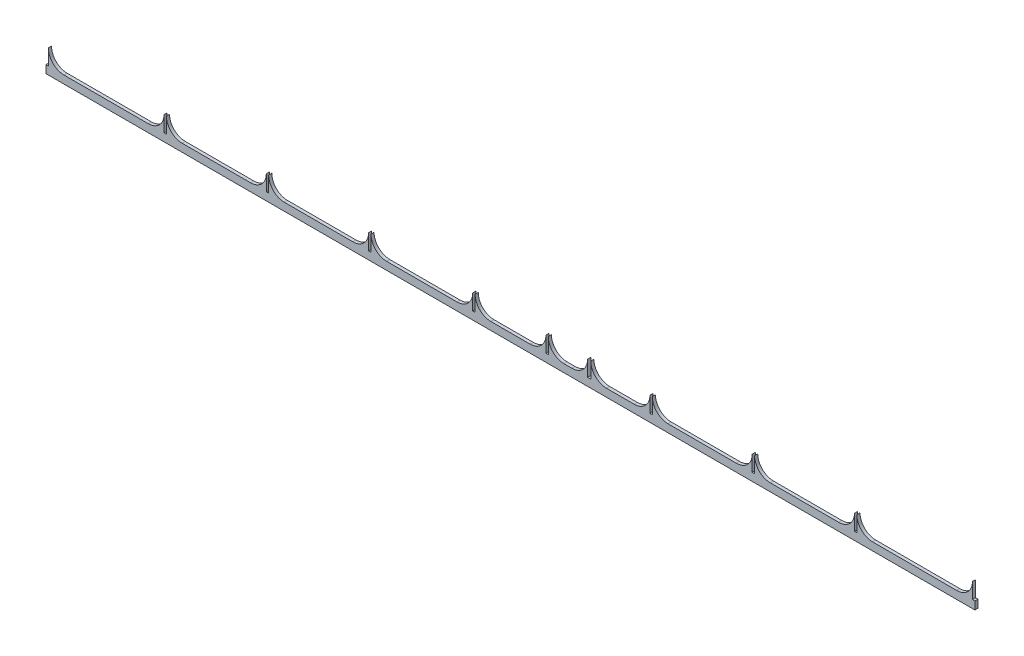
SolidWorks part; units mm, degrees
ref_plane "前视基准面" through (0, 0, 0) normal (0, 0, 1) x (1, 0, 0)
ref_plane "上视基准面" through (0, 0, 0) normal (0, 1, 0) x (1, 0, 0)
ref_plane "右视基准面" through (0, 0, 0) normal (1, 0, 0) x (0, 0, -1)
sketch "Model" plane through (0, 0, 0) normal (0, 0, 1) x (1, 0, 0)
  line L0 (-3.696, 8.7466) -> (49.804, 8.7466)
  line L1 (71.304, 8.7466) -> (114.8039, 8.7466)
  line L2 (275.4749, 8.7466) -> (292.5039, 8.7466)
  line L3 (314.0039, 8.7466) -> (319.0039, 8.7466)
  line L4 (136.3039, 8.7466) -> (179.8039, 8.7466)
  line L5 (201.3039, 8.7466) -> (246.0039, 8.7466)
  line L6 (341.0039, 8.7466) -> (358.6003, 8.7466)
  line L7 (563.6002, 8.7466) -> (510.1002, 8.7466)
  line L8 (488.6002, 8.7466) -> (445.1003, 8.7466)
  line L9 (423.6003, 8.7466) -> (380.1003, 8.7466)
  line L10 (-15.196, 3.7466) -> (-15.196, 8.7466)
  line L11 (-13.696, 18.7466) -> (-13.696, 8.7466)
  line L12 (-15.196, 8.7466) -> (-13.696, 8.7466)
  line L13 (59.804, 18.7466) -> (59.804, 8.7466)
  line L14 (61.304, 18.7466) -> (61.304, 8.7466)
  line L15 (59.804, 8.7466) -> (61.304, 8.7466)
  line L16 (124.8039, 18.7466) -> (124.8039, 8.7466)
  line L17 (126.3039, 18.7466) -> (126.3039, 8.7466)
  line L18 (124.8039, 8.7466) -> (126.3039, 8.7466)
  line L19 (189.8039, 18.7466) -> (189.8039, 8.7466)
  line L20 (191.3039, 18.7466) -> (191.3039, 8.7466)
  line L21 (189.8039, 8.7466) -> (191.3039, 8.7466)
  line L22 (256.0039, 18.7466) -> (256.0039, 8.7466)
  line L23 (257.5039, 18.7466) -> (257.5039, 8.7466)
  line L24 (256.0039, 8.7466) -> (257.5039, 8.7466)
  line L25 (302.5039, 18.7466) -> (302.5039, 8.7466)
  line L26 (304.0039, 18.7466) -> (304.0039, 8.7466)
  line L27 (302.5039, 8.7466) -> (304.0039, 8.7466)
  line L28 (329.0039, 18.7466) -> (329.0039, 8.7466)
  line L29 (329.0039, 8.7466) -> (331.0039, 8.7466)
  line L30 (331.0039, 18.7466) -> (331.0039, 8.7466)
  line L31 (368.6003, 18.7466) -> (368.6003, 8.7466)
  line L32 (370.1003, 18.7466) -> (370.1003, 8.7466)
  line L33 (368.6003, 8.7466) -> (370.1003, 8.7466)
  line L34 (433.6003, 18.7466) -> (433.6003, 8.7466)
  line L35 (435.1003, 18.7466) -> (435.1003, 8.7466)
  line L36 (433.6003, 8.7466) -> (435.1003, 8.7466)
  line L37 (498.6002, 18.7466) -> (498.6002, 8.7466)
  line L38 (500.1002, 18.7466) -> (500.1002, 8.7466)
  line L39 (498.6002, 8.7466) -> (500.1002, 8.7466)
  line L40 (573.6002, 18.7466) -> (573.6002, 8.7466)
  line L41 (575.1002, 3.7466) -> (575.1002, 8.7466)
  line L42 (573.6002, 8.7466) -> (575.1002, 8.7466)
  line L43 (-15.196, 3.7466) -> (575.1002, 3.7466)
  line L44 (267.5039, 8.7466) -> (275.4749, 8.7466)
  arc A0 (61.304, 18.7466) -> (71.304, 8.7466) centre (71.304, 18.7466) ccw
  arc A1 (-13.696, 18.7466) -> (-3.696, 8.7466) centre (-3.696, 18.7466) ccw
  arc A2 (49.804, 8.7466) -> (59.804, 18.7466) centre (49.804, 18.7466) ccw
  arc A3 (114.8039, 8.7466) -> (124.8039, 18.7466) centre (114.8039, 18.7466) ccw
  arc A4 (246.0039, 8.7466) -> (256.0039, 18.7466) centre (246.0039, 18.7466) ccw
  arc A5 (292.5039, 8.7466) -> (302.5039, 18.7466) centre (292.5039, 18.7466) ccw
  arc A6 (319.0039, 8.7466) -> (329.0039, 18.7466) centre (319.0039, 18.7466) ccw
  arc A7 (257.5039, 18.7466) -> (267.5039, 8.7466) centre (267.5039, 18.7466) ccw
  arc A8 (304.0039, 18.7466) -> (314.0039, 8.7466) centre (314.0039, 18.7466) ccw
  arc A9 (331.0039, 18.7466) -> (341.0039, 8.7466) centre (341.0039, 18.7466) ccw
  arc A10 (126.3039, 18.7466) -> (136.3039, 8.7466) centre (136.3039, 18.7466) ccw
  arc A11 (179.8039, 8.7466) -> (189.8039, 18.7466) centre (179.8039, 18.7466) ccw
  arc A12 (191.3039, 18.7466) -> (201.3039, 8.7466) centre (201.3039, 18.7466) ccw
  arc A13 (488.6002, 8.7466) -> (498.6002, 18.7466) centre (488.6002, 18.7466) ccw
  arc A14 (563.6002, 8.7466) -> (573.6002, 18.7466) centre (563.6002, 18.7466) ccw
  arc A15 (500.1002, 18.7466) -> (510.1002, 8.7466) centre (510.1002, 18.7466) ccw
  arc A16 (435.1003, 18.7466) -> (445.1003, 8.7466) centre (445.1003, 18.7466) ccw
  arc A17 (423.6003, 8.7466) -> (433.6003, 18.7466) centre (423.6003, 18.7466) ccw
  arc A18 (370.1003, 18.7466) -> (380.1003, 8.7466) centre (380.1003, 18.7466) ccw
  arc A19 (358.6003, 8.7466) -> (368.6003, 18.7466) centre (358.6003, 18.7466) ccw
extrude "凸台-拉伸1" add sketch "Model" along normal blind 2
